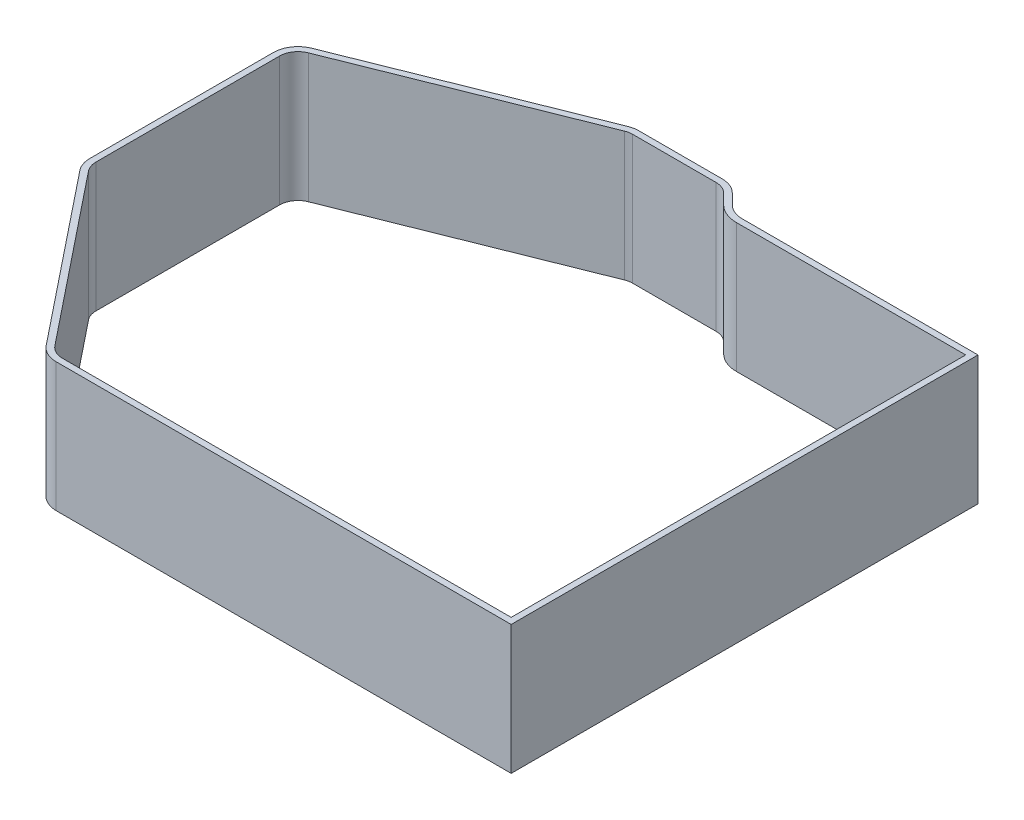
SolidWorks part; units mm, degrees
ref_plane "Plano frontal" through (0, 0, 0) normal (0, 0, 1) x (1, 0, 0)
ref_plane "Plano superior" through (0, 0, 0) normal (0, 1, 0) x (1, 0, 0)
ref_plane "Plano direito" through (0, 0, 0) normal (1, 0, 0) x (0, 0, -1)
sketch "Esboço2" plane through (0, 2101.5213, 0) normal (0, -1, 0) x (1, 0, 0)
  line L0 (1583.1904, 82.7287) -> (1546.1516, 82.7287)
  line L1 (1544.5899, 81.9781) -> (1533.6286, 68.2766)
  line L2 (1533.1904, 67.0272) -> (1533.1904, 52.0828)
  line L4 (1534.4476, 50.2258) -> (1552.8327, 42.8718)
  line L6 (1560.3619, 42.7287) -> (1553.5755, 42.7287) construction
  line L7 (1553.5755, 42.7287) -> (1560.3619, 42.7287)
  line L9 (1561.7761, 43.3145) -> (1562.6046, 44.1429)
  line L11 (1564.0188, 44.7287) -> (1583.1904, 44.7287)
  line L12 (1583.1904, 44.7287) -> (1583.1904, 82.7287)
  line L13 (1564.0188, 45.2287) -> (1582.6904, 45.2287)
  line L14 (1582.6904, 45.2287) -> (1582.6904, 82.2287)
  line L15 (1582.6904, 82.2287) -> (1546.1516, 82.2287)
  line L16 (1544.9803, 81.6658) -> (1534.0191, 67.9642)
  line L17 (1533.6904, 67.0272) -> (1533.6904, 52.0828)
  line L18 (1534.6333, 50.6901) -> (1553.0184, 43.336)
  line L19 (1553.5755, 43.2287) -> (1560.3619, 43.2287)
  line L20 (1561.4226, 43.6681) -> (1562.251, 44.4965)
  arc A0 (1552.8327, 42.8718) -> (1553.5755, 42.7287) centre (1553.5755, 44.7287) ccw construction
  arc A1 (1546.1516, 82.7287) -> (1544.5899, 81.9781) centre (1546.1516, 80.7287) ccw
  arc A2 (1533.6286, 68.2766) -> (1533.1904, 67.0272) centre (1535.1904, 67.0272) ccw
  arc A3 (1533.1904, 52.0828) -> (1534.4476, 50.2258) centre (1535.1904, 52.0828) ccw
  arc A4 (1552.8327, 42.8718) -> (1553.5755, 42.7287) centre (1553.5755, 44.7287) ccw
  arc A5 (1561.7761, 43.3145) -> (1560.3619, 42.7287) centre (1560.3619, 44.7287) cw
  arc A6 (1562.6046, 44.1429) -> (1564.0188, 44.7287) centre (1564.0188, 42.7287) cw
  circle A7 centre (1556.1904, 47.7287) radius 1.5
  circle A8 centre (1558.1904, 54.2287) radius 1.5
  circle A9 centre (1558.1904, 69.2287) radius 1.5
  circle A10 centre (1537.1904, 56.7287) radius 1.5
  circle A11 centre (1537.1904, 56.7287) radius 2.5
  arc A12 (1562.251, 44.4965) -> (1564.0188, 45.2287) centre (1564.0188, 42.7287) cw
  arc A13 (1546.1516, 82.2287) -> (1544.9803, 81.6658) centre (1546.1516, 80.7287) ccw
  arc A14 (1534.0191, 67.9642) -> (1533.6904, 67.0272) centre (1535.1904, 67.0272) ccw
  arc A15 (1533.6904, 52.0828) -> (1534.6333, 50.6901) centre (1535.1904, 52.0828) ccw
  arc A16 (1553.0184, 43.336) -> (1553.5755, 43.2287) centre (1553.5755, 44.7287) ccw
  arc A17 (1561.4226, 43.6681) -> (1560.3619, 43.2287) centre (1560.3619, 44.7287) cw
  circle M30 centre (1558.1904, 69.2287) radius 1.5
  circle M31 centre (1558.1904, 54.2287) radius 1.5
  circle M32 centre (1556.1904, 47.7287) radius 1.5
  dimension "D1" = 1
  dimension "D2" = 0.5
extrude "Ressalto-extrusão3" add sketch "Esboço2" against normal blind 10.5 contours A17 L20 A12 L13 L14 L15 A13 L16 A14 L17 A15 L18 A16 L19 A11 M31 M32 M30 | L11 L12 L0 A1 L1 A2 L2 A3 L4 A4 L7 A5 L9 A6
